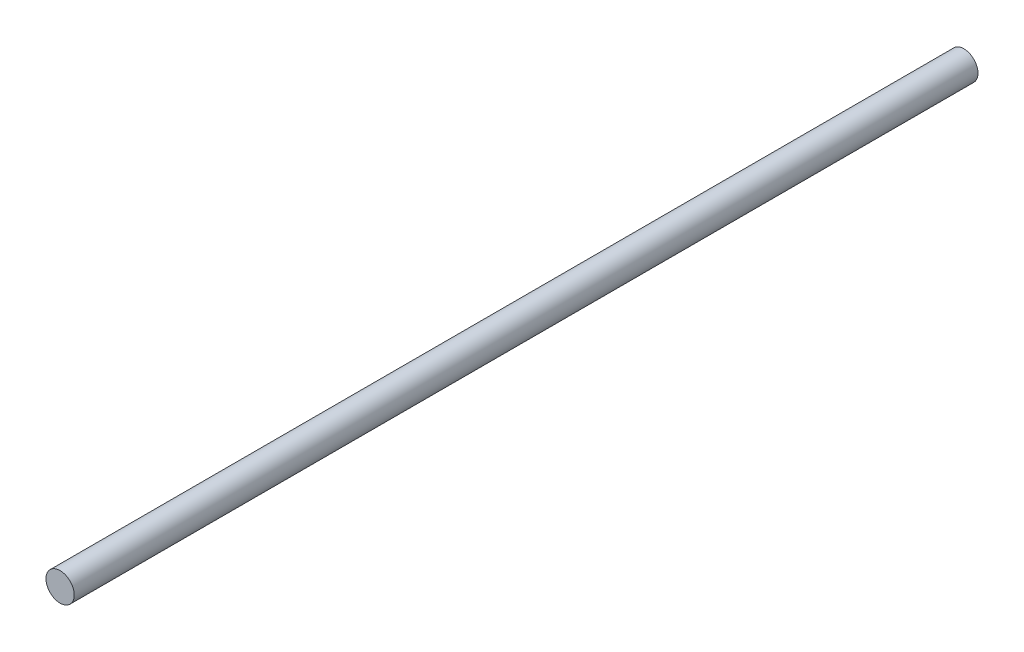
SolidWorks part; units mm, degrees
ref_plane "Plan de face" through (0, 0, 0) normal (0, 0, 1) x (1, 0, 0)
ref_plane "Plan de dessus" through (0, 0, 0) normal (0, 1, 0) x (1, 0, 0)
ref_plane "Plan de droite" through (0, 0, 0) normal (1, 0, 0) x (0, 0, -1)
sketch "Esquisse1" plane through (0, 0, 0) normal (0, 0, 1) x (1, 0, 0)
  circle A0 centre (0, 0) radius 1.5875
  dimension "D1" = 3.175
extrude "Boss.-Extru.1" add sketch "Esquisse1" along normal blind 101.6
